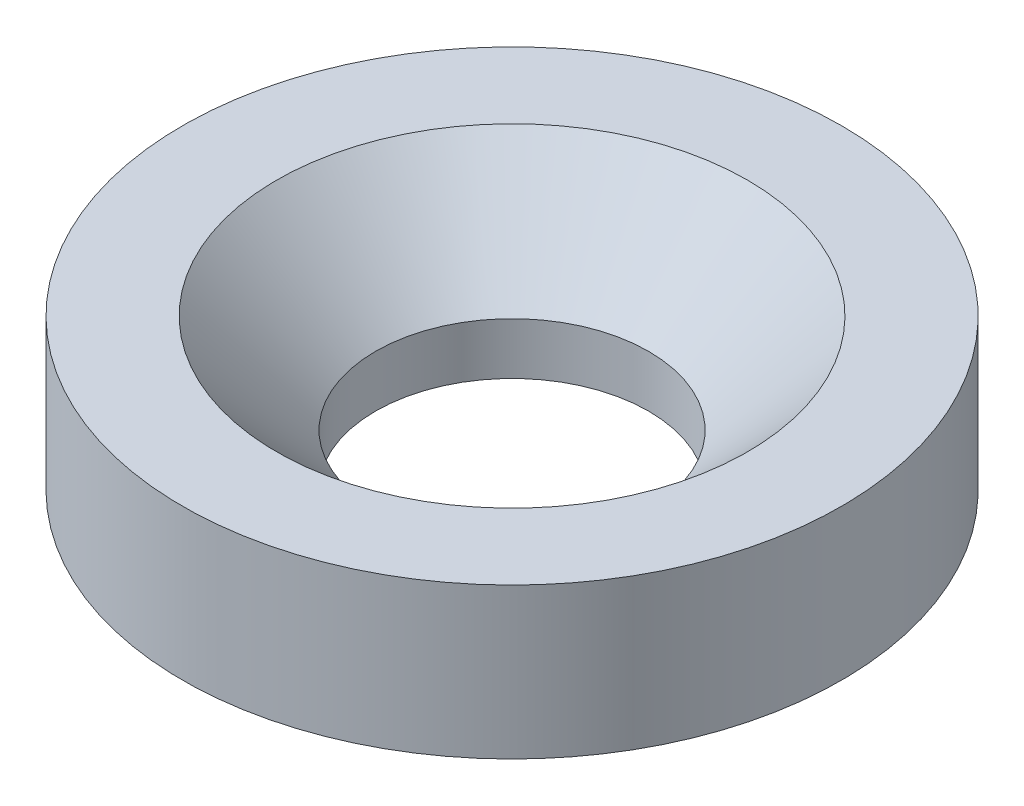
SolidWorks part; units mm, degrees
material "AISI 1020"
ref_plane "Front Plane" through (0, 0, 0) normal (0, 0, 1) x (1, 0, 0)
ref_plane "Top Plane" through (0, 0, 0) normal (0, 1, 0) x (1, 0, 0)
ref_plane "Right Plane" through (0, 0, 0) normal (1, 0, 0) x (0, 0, -1)
sketch "Sketch1" plane through (0, 0, 0) normal (0, 0, 1) x (1, 0, 0)
  line L0 (7.25, 0) -> (17.5, 0)
  line L1 (17.5, 0) -> (17.5, 8)
  line L2 (17.5, 8) -> (12.5, 8)
  line L3 (12.5, 8) -> (7.25, 2.75)
  line L4 (7.25, 2.75) -> (7.25, 0)
  line L5 (0, 0) -> (0, 17.8054) construction
  dimension "D1" = 17.5
  dimension "D2" = 7.25
  dimension "D3" = 12.5
  dimension "D4" = 8
  dimension "D5" = 45
revolve "Revolve1" add sketch "Sketch1" angle 360 about L5
